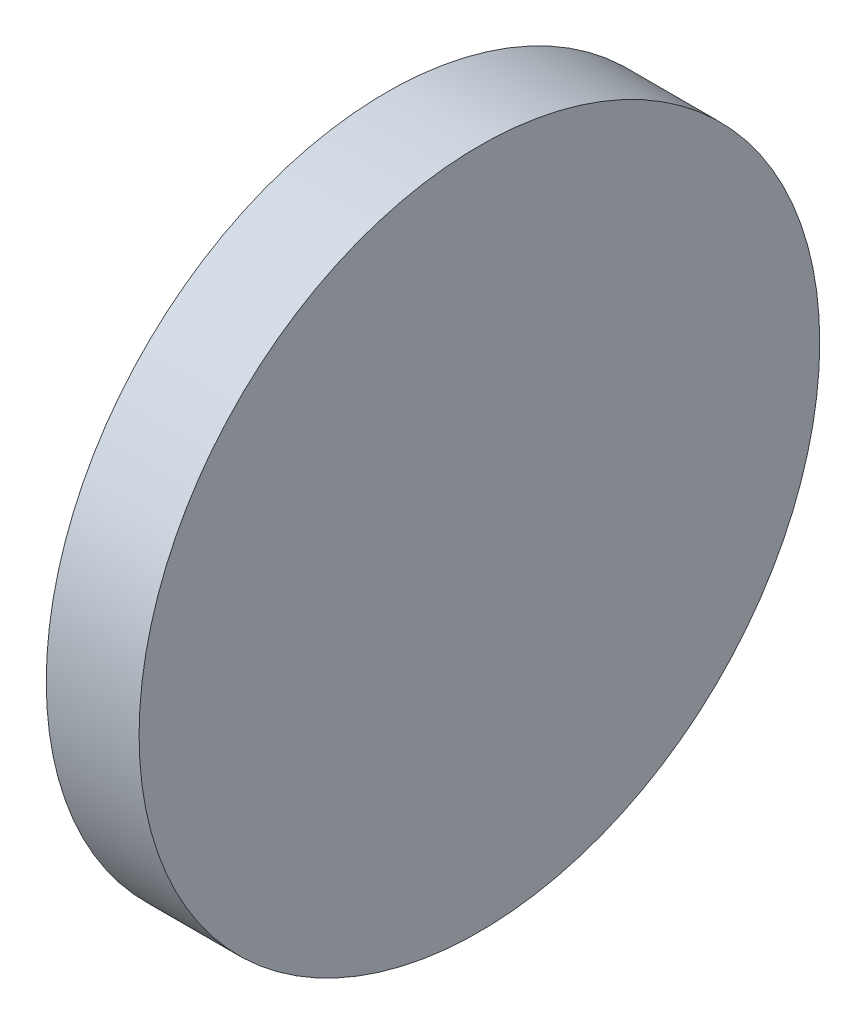
SolidWorks part; units mm, degrees
ref_plane "Front Plane" through (0, 0, 0) normal (0, 0, 1) x (1, 0, 0)
ref_plane "Top Plane" through (0, 0, 0) normal (0, 1, 0) x (1, 0, 0)
ref_plane "Right Plane" through (0, 0, 0) normal (1, 0, 0) x (0, 0, -1)
sketch "Sketch3" plane through (0, 0, 0) normal (1, 0, 0) x (0, 0, -1)
  circle A0 centre (0, 0) radius 55
extrude "Boss-Extrude2" add sketch "Sketch3" along normal blind 15
